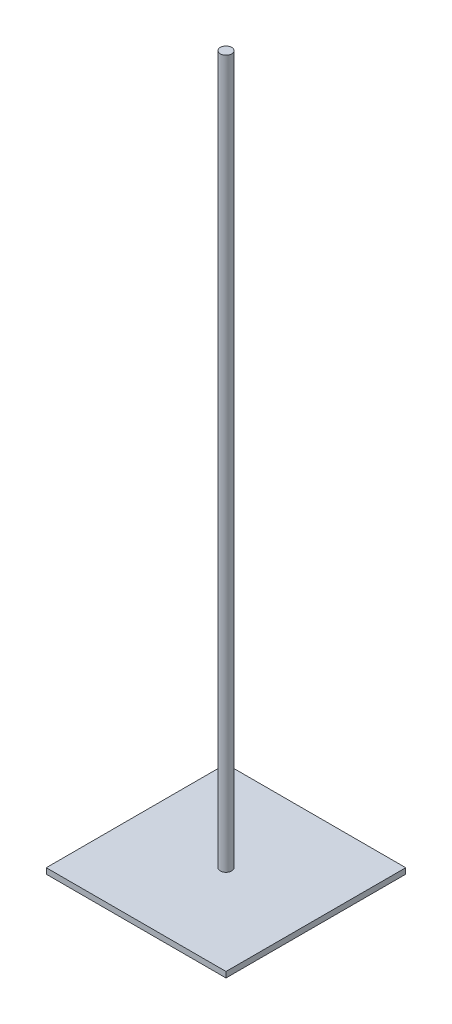
SolidWorks part; units mm, degrees
ref_plane "Front Plane" through (0, 0, 0) normal (0, 0, 1) x (1, 0, 0)
ref_plane "Top Plane" through (0, 0, 0) normal (0, 1, 0) x (1, 0, 0)
ref_plane "Right Plane" through (0, 0, 0) normal (1, 0, 0) x (0, 0, -1)
sketch "Sketch1" plane through (0, 0, 0) normal (0, 1, 0) x (1, 0, 0)
  line L1 (0, 0) -> (-127, 0)
  line L2 (0, 0) -> (0, -127)
  line L3 (0, -127) -> (-127, -127)
  line L4 (-127, 0) -> (-127, -127)
  dimension "D1" = 127
  dimension "D2" = 127
extrude "Boss-Extrude1" add sketch "Sketch1" along normal blind 4
sketch "Sketch2" plane through (0, 4, 0) normal (0, 1, 0) x (1, 0, 0)
  line L0 (-63.5, 0) -> (-63.5, -127) construction
  line L1 (0, 0) -> (-127, 0) construction
  line L2 (-127, -127) -> (0, -127) construction
  circle A0 centre (-63.5, -63.5) radius 4
  dimension "D1" = 8
extrude "Boss-Extrude2" add sketch "Sketch2" along normal blind 500 separate body
